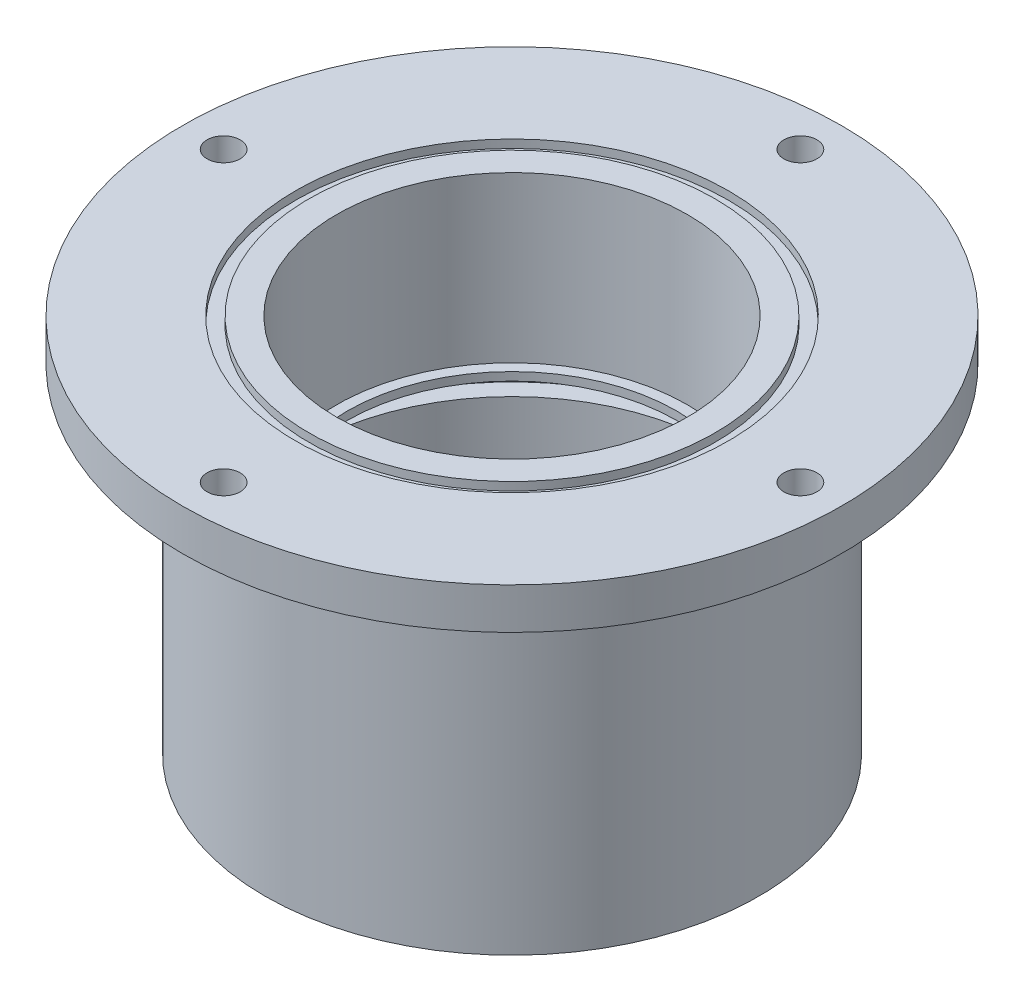
SolidWorks part; units mm, degrees
material "6063-T6"
ref_plane "Front Plane" through (0, 0, 0) normal (0, 0, 1) x (1, 0, 0)
ref_plane "Top Plane" through (0, 0, 0) normal (0, 1, 0) x (1, 0, 0)
ref_plane "Right Plane" through (0, 0, 0) normal (1, 0, 0) x (0, 0, -1)
sketch "Sketch1" plane through (0, 0, 0) normal (0, 0, 1) x (1, 0, 0)
  line L0 (31.8135, 0) -> (38.1, 0)
  line L1 (38.1, 0) -> (38.1, 52.07)
  line L2 (50.8, 58.42) -> (50.8, 52.07)
  line L3 (0, 0) -> (0, 126.8048) construction
  line L4 (25.4, 31.75) -> (31.8135, 31.75)
  line L5 (31.8135, 31.75) -> (31.8135, 28.702)
  line L6 (31.8135, 2.54) -> (33.909, 2.54)
  line L7 (33.909, 2.54) -> (33.909, 6.096)
  line L8 (33.909, 6.096) -> (31.8135, 6.096)
  line L9 (31.8135, 25.146) -> (34.583, 25.146)
  line L10 (34.583, 25.146) -> (34.583, 28.702)
  line L11 (34.583, 28.702) -> (31.8135, 28.702)
  line L12 (27.051, 33.02) -> (27.051, 58.42)
  line L13 (25.4, 31.75) -> (25.4, 33.02)
  line L14 (25.4, 33.02) -> (27.051, 33.02)
  line L15 (27.051, 58.42) -> (31.2801, 58.42)
  line L18 (31.2801, 58.42) -> (31.2801, 57.15)
  line L19 (31.2801, 57.15) -> (33.3883, 57.15)
  line L20 (33.3883, 57.15) -> (33.3883, 58.42)
  line L21 (38.1, 52.07) -> (50.8, 52.07)
  line L24 (33.3883, 58.42) -> (50.8, 58.42)
  line L26 (31.8135, 25.146) -> (31.8135, 6.096)
  line L27 (31.8135, 2.54) -> (31.8135, 0)
  dimension "D1" = 67.818
  dimension "D2" = 63.627
  dimension "D3" = 3.556
  dimension "D4" = 3.556
  dimension "D5" = 2.54
  dimension "D6" = 3.048
  dimension "D7" = 31.75
  dimension "D8" = 54.102
  dimension "D9" = 50.8
  dimension "D10" = 1.27
  dimension "D11" = 58.42
  dimension "D13" = 6.35
  dimension "D14" = 76.2
  dimension "D15" = 2.1082
  dimension "D16" = 1.27
  dimension "D17" = 66.7766
  dimension "D18" = 50.8
revolve "Revolve1" add sketch "Sketch1" angle 360 about L3
hole_wizard "Tapped Hole for #10-32 Helicoil1" positions "Sketch3" profile "Sketch2" tap size "#10-32" standard "Helicoil® Inch" end condition up to next
sketch "Sketch3" plane through (0, 58.42, 0) normal (0, 1, 0) x (1, 0, 0)
  circle A0 centre (0, 0) radius 27.051 construction
  point P0 (0, 44.45)
  dimension "D1" = 44.45
sketch "Sketch2" plane through (0, 58.42, -44.45) normal (1, 0, 0) x (0, 0, 1)
  line L0 (0, 0) -> (0, 6.351)
  line L1 (0, 6.351) -> (2.5527, 6.351)
  line L2 (2.5527, 6.351) -> (2.5527, 0)
  line L5 (2.5527, 0) -> (0, 0)
  line L11 (0, -6.35) -> (0, 107.95) construction
  dimension "Thru Tap Drill Dia." = 5.1054
  dimension "Thru Tap Drill Depth" = 6.351
cosmetic thread "Hole Thread1" parameters "D1"=5.588, "D2"=5.936
sketch "Sketch4" plane through (0, 58.42, 0) normal (0, 1, 0) x (1, 0, 0)
  line L0 (0, -6.35) -> (0, 63.5) construction
  circle A0 centre (0, 44.45) radius 2.5527 construction
  dimension "D1" = 50.8
pattern_circular "CirPattern1" count 4 over 360 about axis through (0, 0, 0) along (0, 1, 0) of "Tapped Hole for #10-32 Helicoil1"
